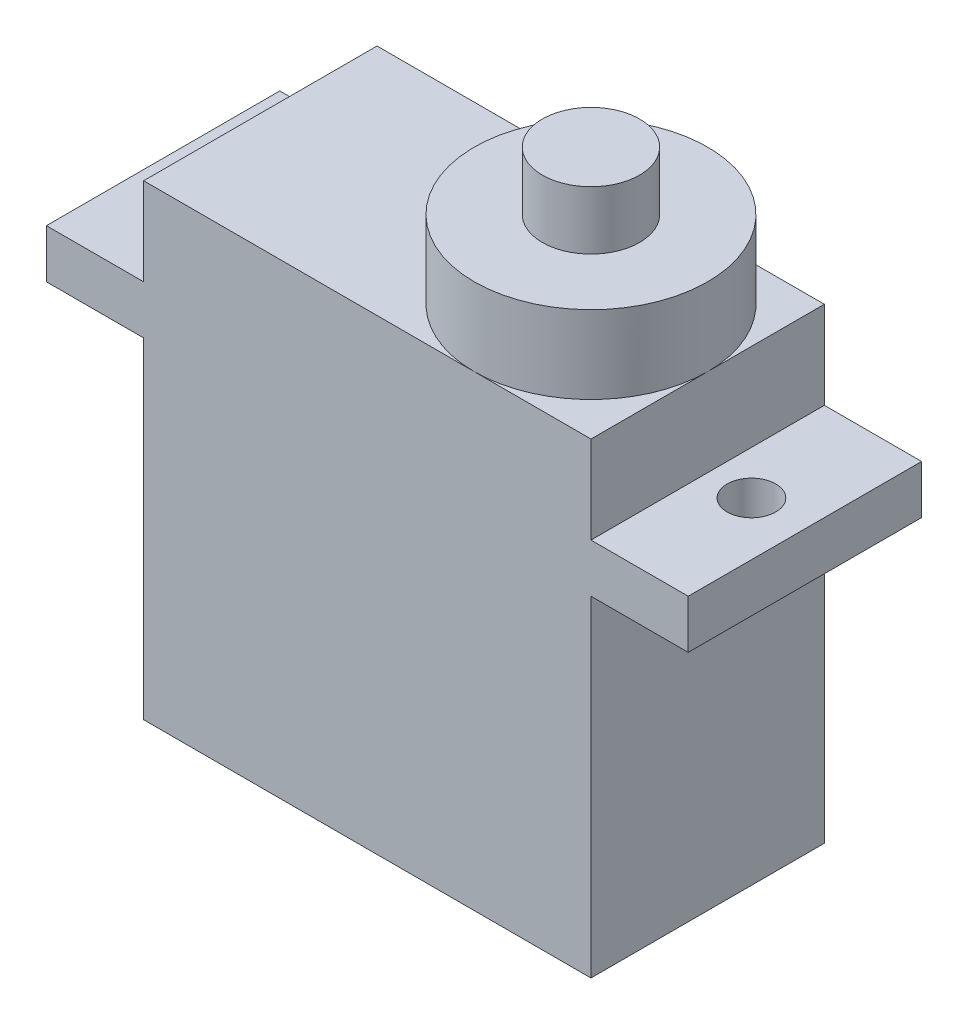
SolidWorks part; units mm, degrees
ref_plane "前视基准面" through (0, 0, 0) normal (0, 0, 1) x (1, 0, 0)
ref_plane "上视基准面" through (0, 0, 0) normal (0, 1, 0) x (1, 0, 0)
ref_plane "右视基准面" through (0, 0, 0) normal (1, 0, 0) x (0, 0, -1)
sketch "草图1" plane through (0, 0, 0) normal (0, 1, 0) x (1, 0, 0)
  line L1 (-11.5, 6) -> (11.5, 6)
  line L2 (-11.5, 6) -> (-11.5, -6)
  line L3 (-11.5, -6) -> (11.5, -6)
  line L4 (11.5, 6) -> (11.5, -6)
  line L5 (-11.5, 6) -> (11.5, -6) construction
  line L6 (-11.5, -6) -> (11.5, 6) construction
  point P0 (0, 0)
  dimension "D1" = 23
  dimension "D2" = 12
extrude "凸台-拉伸1" add sketch "草图1" along normal blind 24
sketch "草图2" plane through (11.5, 0, 0) normal (1, 0, 0) x (0, 0, -1)
  line L0 (6, 24) -> (6, 0) construction
  line L1 (-6, 19.5) -> (6, 19.5)
  line L2 (-6, 19.5) -> (-6, 17)
  line L3 (-6, 17) -> (6, 17)
  line L4 (6, 19.5) -> (6, 17)
  line L5 (-6, 19.5) -> (6, 17) construction
  line L6 (-6, 17) -> (6, 19.5) construction
  line L8 (-6, 24) -> (6, 24) construction
  line L9 (-6, 24) -> (-6, 0) construction
  point P0 (0, 18.25)
  point P7 (0.3897, 18.25)
  dimension "D1" = 2.5
  dimension "D2" = 4.5
extrude "凸台-拉伸2" add sketch "草图2" along normal blind 5
sketch "草图3" plane through (-11.5, 0, 0) normal (-1, 0, 0) x (0, 0, 1)
  line L0 (6, 24) -> (6, 0) construction
  line L1 (-6, 19.5) -> (6, 19.5)
  line L2 (-6, 19.5) -> (-6, 17)
  line L3 (-6, 17) -> (6, 17)
  line L4 (6, 19.5) -> (6, 17)
  line L5 (-6, 19.5) -> (6, 17) construction
  line L6 (-6, 17) -> (6, 19.5) construction
  line L7 (-6, 24) -> (6, 24) construction
  line L8 (-6, 24) -> (-6, 0) construction
  point P0 (0, 18.25)
  dimension "D1" = 2.5
  dimension "D2" = 4.5
extrude "凸台-拉伸3" add sketch "草图3" along normal blind 5
sketch "草图4" plane through (0, 24, 0) normal (0, 1, 0) x (1, 0, 0)
  line L0 (11.5, 6) -> (-11.5, 6) construction
  line L1 (11.5, -6) -> (11.5, 6) construction
  circle A0 centre (5.5, 0) radius 6
  dimension "D1" = 12
extrude "凸台-拉伸4" add sketch "草图4" along normal blind 4
sketch "草图5" plane through (0, 28, 0) normal (0, 1, 0) x (1, 0, 0)
  circle A0 centre (5.5, 0) radius 2.5
  circle A1 centre (5.5, 0) radius 6 construction
  dimension "D1" = 5
extrude "凸台-拉伸5" add sketch "草图5" along normal blind 3
sketch "草图6" plane through (0, 19.5, 0) normal (0, 1, 0) x (1, 0, 0)
  line L0 (11.5, 0) -> (11.5, 6) construction
  line L1 (-11.5, -6) -> (-11.5, 6) construction
  line L2 (16.5, 6) -> (11.5, 6) construction
  circle A0 centre (13.75, 0) radius 1.25
  circle A1 centre (-13.75, 0) radius 1.25
  point P8 (0, 0)
  point P9 (0, 0)
  dimension "D1" = 2.5
  dimension "D2" = 2.5
  dimension "D3" = 2.25
  dimension "D4" = 2.25
  dimension "D5" = 6
extrude "切除-拉伸1" cut sketch "草图6" against normal blind 3
